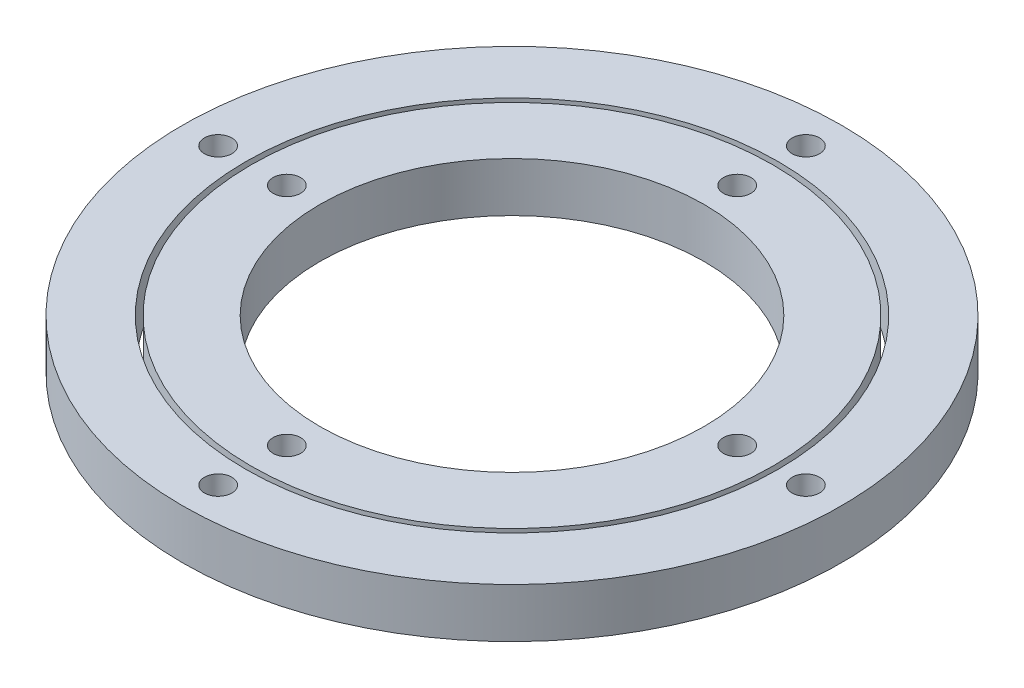
SolidWorks part; units mm, degrees
ref_plane "前视基准面" through (0, 0, 0) normal (0, 0, 1) x (1, 0, 0)
ref_plane "上视基准面" through (0, 0, 0) normal (0, 1, 0) x (1, 0, 0)
ref_plane "右视基准面" through (0, 0, 0) normal (1, 0, 0) x (0, 0, -1)
other "Configuration Table"
sketch "草图1" plane through (0, 0, 0) normal (0, 1, 0) x (1, 0, 0)
  line L0 (0, 0) -> (0, -47.5) construction
  line L1 (0, 0) -> (33.5876, -33.5876) construction
  line L2 (0, 0) -> (47.5, 0) construction
  line L3 (0, 0) -> (-47.5, 0) construction
  circle A0 centre (0, 0) radius 35
  circle A1 centre (0, 0) radius 47.5
  circle A2 centre (-41, 0) radius 2.5
  circle A3 centre (41, 0) radius 2.5
  circle A4 centre (0, -41) radius 2.5
  circle A5 centre (0, 41) radius 2.5
  dimension "D1" = 70
  dimension "D2" = 95
  dimension "D5" = 5
  dimension "D3" = 41
  dimension "D4" = 45
extrude "凸台-拉伸1" add sketch "草图1" along normal blind 9
sketch "草图2" plane through (0, 0, 0) normal (0, -1, 0) x (1, 0, 0)
  line L0 (0, 0) -> (0, 60) construction
  line L1 (0, 60) -> (0, -60) construction
  line L2 (0, -60) -> (0, 0) construction
  line L3 (0, 0) -> (60, 0) construction
  line L4 (60, 0) -> (-60, 0) construction
  line L5 (0, 0) -> (42.4264, -42.4264) construction
  line L6 (42.4264, -42.4264) -> (-42.4264, 42.4264) construction
  circle A0 centre (0, 0) radius 48.5
  circle A1 centre (0, 0) radius 60
  circle A3 centre (0, 53.5) radius 2.5
  circle A4 centre (-53.5, 0) radius 2.5
  circle A5 centre (0, -53.5) radius 2.5
  circle A6 centre (53.5, 0) radius 2.5
  dimension "D1" = 97
  dimension "D2" = 120
  dimension "D4" = 53.5
  dimension "D5" = 5
  dimension "D3" = 45
extrude "凸台-拉伸2" add sketch "草图2" against normal blind 9 separate body
equation "\"9mian\"=10"
